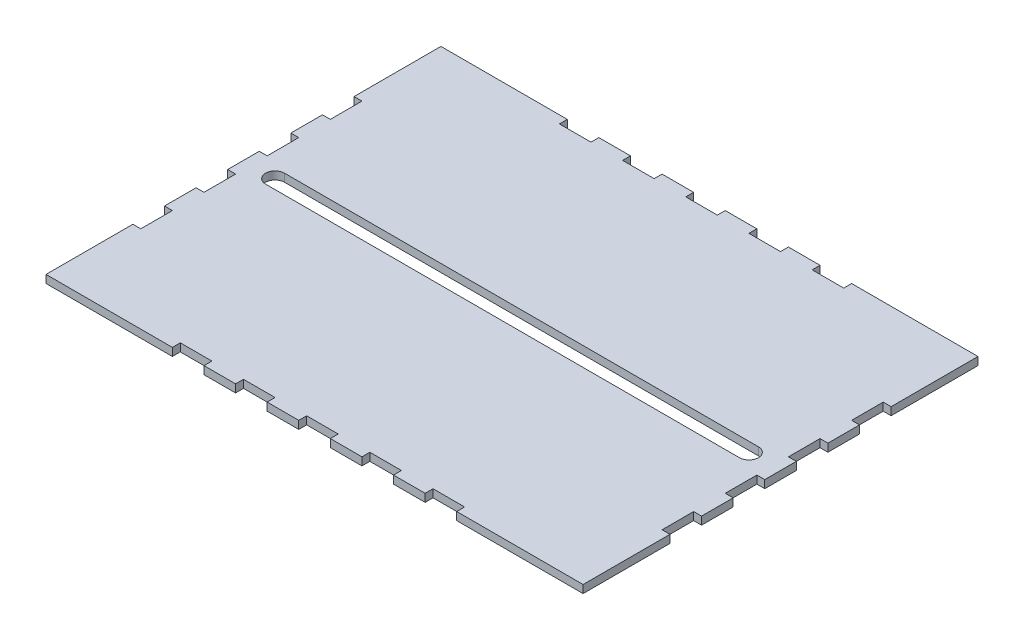
SolidWorks part; units mm, degrees
ref_plane "Front Plane" through (0, 0, 0) normal (0, 0, 1) x (1, 0, 0)
ref_plane "Top Plane" through (0, 0, 0) normal (0, 1, 0) x (1, 0, 0)
ref_plane "Right Plane" through (0, 0, 0) normal (1, 0, 0) x (0, 0, -1)
sketch "Sketch1" plane through (0, 0, 0) normal (0, 1, 0) x (1, 0, 0)
  line L0 (-14.0646, -39.6932) -> (-14.0646, 76.1041) construction
  line L3 (-122.0146, 89.7166) -> (-71.2146, 89.7166)
  line L5 (43.0854, -69.0334) -> (93.8854, -69.0334)
  line L6 (-122.0146, 89.7166) -> (93.8854, -69.0334) construction
  line L7 (-122.0146, 10.3416) -> (53.3287, 10.3416) construction
  line L8 (-20.4146, 89.7166) -> (-20.4146, 86.5416)
  line L9 (-20.4146, 86.5416) -> (-7.7146, 86.5416)
  line L10 (-7.7146, 86.5416) -> (-7.7146, 89.7166)
  line L11 (-33.1146, 89.7166) -> (-33.1146, 86.5416)
  line L12 (-33.1146, 86.5416) -> (-45.8146, 86.5416)
  line L13 (-45.8146, 86.5416) -> (-45.8146, 89.7166)
  line L14 (-58.5146, 89.7166) -> (-58.5146, 86.5416)
  line L15 (-58.5146, 86.5416) -> (-71.2146, 86.5416)
  line L16 (-71.2146, 86.5416) -> (-71.2146, 89.7166)
  line L17 (-58.5146, 89.7166) -> (-45.8146, 89.7166)
  line L18 (-33.1146, 89.7166) -> (-20.4146, 89.7166)
  line L19 (-7.7146, 89.7166) -> (4.9854, 89.7166)
  line L20 (4.9854, 89.7166) -> (4.9854, 86.5416)
  line L21 (4.9854, 86.5416) -> (17.6854, 86.5416)
  line L22 (17.6854, 86.5416) -> (17.6854, 89.7166)
  line L23 (30.3854, 89.7166) -> (30.3854, 86.5416)
  line L24 (30.3854, 86.5416) -> (43.0854, 86.5416)
  line L25 (43.0854, 86.5416) -> (43.0854, 89.7166)
  line L26 (17.6854, 89.7166) -> (30.3854, 89.7166)
  line L27 (43.0854, 89.7166) -> (93.8854, 89.7166)
  line L29 (-122.0146, 54.7916) -> (-118.8396, 54.7916)
  line L30 (-118.8396, 54.7916) -> (-118.8396, 42.0916)
  line L31 (-118.8396, 42.0916) -> (-122.0146, 42.0916)
  line L32 (-122.0146, 42.0916) -> (-122.0146, 29.3916)
  line L33 (-122.0146, 29.3916) -> (-118.8396, 29.3916)
  line L34 (-118.8396, 29.3916) -> (-118.8396, 16.6916)
  line L35 (-118.8396, 16.6916) -> (-122.0146, 16.6916)
  line L36 (-122.0146, 16.6916) -> (-122.0146, 3.9916)
  line L37 (-122.0146, 3.9916) -> (-118.8396, 3.9916)
  line L38 (-118.8396, 3.9916) -> (-118.8396, -8.7084)
  line L39 (-118.8396, -8.7084) -> (-122.0146, -8.7084)
  line L40 (-122.0146, -8.7084) -> (-122.0146, -21.4084)
  line L41 (-122.0146, -21.4084) -> (-118.8396, -21.4084)
  line L42 (-118.8396, -21.4084) -> (-118.8396, -34.1084)
  line L43 (-118.8396, -34.1084) -> (-122.0146, -34.1084)
  line L44 (-122.0146, -34.1084) -> (-122.0146, -69.0334)
  line L48 (-122.0146, 54.7916) -> (-122.0146, 89.7166)
  line L49 (17.6854, -69.0334) -> (30.3854, -69.0334)
  line L50 (43.0854, -65.8584) -> (43.0854, -69.0334)
  line L51 (30.3854, -65.8584) -> (43.0854, -65.8584)
  line L52 (30.3854, -69.0334) -> (30.3854, -65.8584)
  line L53 (17.6854, -65.8584) -> (17.6854, -69.0334)
  line L54 (4.9854, -65.8584) -> (17.6854, -65.8584)
  line L55 (4.9854, -69.0334) -> (4.9854, -65.8584)
  line L56 (-7.7146, -69.0334) -> (4.9854, -69.0334)
  line L57 (-33.1146, -69.0334) -> (-20.4146, -69.0334)
  line L58 (-58.5146, -69.0334) -> (-45.8146, -69.0334)
  line L59 (-71.2146, -65.8584) -> (-71.2146, -69.0334)
  line L60 (-58.5146, -65.8584) -> (-71.2146, -65.8584)
  line L61 (-58.5146, -69.0334) -> (-58.5146, -65.8584)
  line L62 (-45.8146, -65.8584) -> (-45.8146, -69.0334)
  line L63 (-33.1146, -65.8584) -> (-45.8146, -65.8584)
  line L64 (-33.1146, -69.0334) -> (-33.1146, -65.8584)
  line L65 (-7.7146, -65.8584) -> (-7.7146, -69.0334)
  line L66 (-20.4146, -65.8584) -> (-7.7146, -65.8584)
  line L67 (-20.4146, -69.0334) -> (-20.4146, -65.8584)
  line L68 (-122.0146, -69.0334) -> (-71.2146, -69.0334)
  line L69 (93.8854, 54.7916) -> (93.8854, 89.7166)
  line L70 (93.8854, -34.1084) -> (93.8854, -69.0334)
  line L71 (90.7104, -34.1084) -> (93.8854, -34.1084)
  line L72 (90.7104, -21.4084) -> (90.7104, -34.1084)
  line L73 (93.8854, -21.4084) -> (90.7104, -21.4084)
  line L74 (93.8854, -8.7084) -> (93.8854, -21.4084)
  line L75 (90.7104, -8.7084) -> (93.8854, -8.7084)
  line L76 (90.7104, 3.9916) -> (90.7104, -8.7084)
  line L77 (93.8854, 3.9916) -> (90.7104, 3.9916)
  line L78 (93.8854, 16.6916) -> (93.8854, 3.9916)
  line L79 (90.7104, 16.6916) -> (93.8854, 16.6916)
  line L80 (90.7104, 29.3916) -> (90.7104, 16.6916)
  line L81 (93.8854, 29.3916) -> (90.7104, 29.3916)
  line L82 (93.8854, 42.0916) -> (93.8854, 29.3916)
  line L83 (90.7104, 42.0916) -> (93.8854, 42.0916)
  line L84 (90.7104, 54.7916) -> (90.7104, 42.0916)
  line L85 (93.8854, 54.7916) -> (90.7104, 54.7916)
  point P0 (0, 0)
  dimension "D1" = 12.7
  dimension "D2" = 6.35
  dimension "D3" = 12.7
  dimension "D4" = 3.175
  dimension "D5" = 3.175
  dimension "D6" = 12.7
  dimension "D7" = 12.7
  dimension "D8" = 158.75
  dimension "D9" = 215.9
extrude "Boss-Extrude1" add sketch "Sketch1" along normal mid plane 3.175
sketch "Sketch2" plane through (0, 1.5875, 0) normal (0, 1, 0) x (1, 0, 0)
  line L0 (93.8854, 10.3416) -> (-122.0146, 10.3416) construction
  line L1 (93.8854, 3.9916) -> (93.8854, 16.6916) construction
  line L2 (-122.0146, 16.6916) -> (-122.0146, 3.9916) construction
  line L3 (-14.0646, -69.0334) -> (-14.0646, 89.7166) construction
  line L4 (-20.4146, -69.0334) -> (-7.7146, -69.0334) construction
  line L5 (-20.4146, 89.7166) -> (-7.7146, 89.7166) construction
  line L6 (81.1854, 10.3416) -> (-109.3146, 10.3416) construction
  line L7 (81.1854, 6.5316) -> (-109.3146, 6.5316)
  line L8 (81.1854, 14.1516) -> (-109.3146, 14.1516)
  arc A0 (81.1854, 6.5316) -> (81.1854, 14.1516) centre (81.1854, 10.3416) ccw
  arc A1 (-109.3146, 14.1516) -> (-109.3146, 6.5316) centre (-109.3146, 10.3416) ccw
  point P14 (-14.0646, 10.3416)
  dimension "D2" = 190.5
  dimension "D1" = 7.62
  dimension "D3" = 0
extrude "Cut-Extrude1" cut sketch "Sketch2" against normal through all
